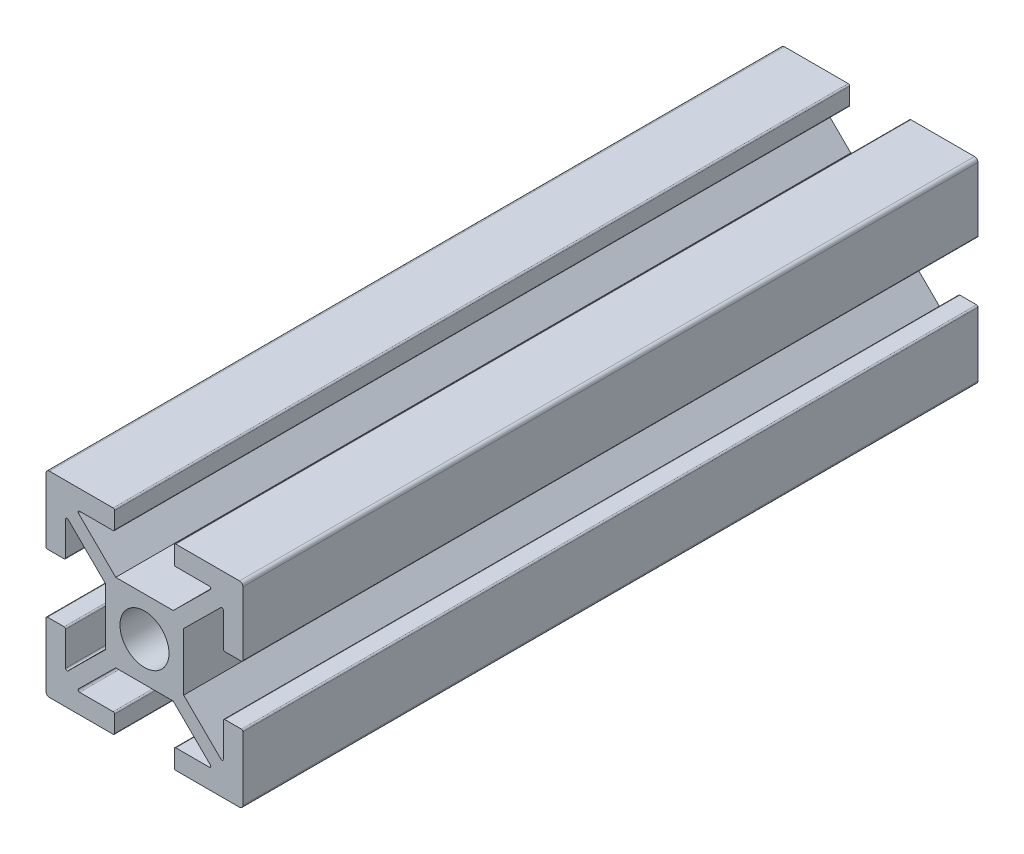
SolidWorks part; units mm, degrees
ref_plane "Front Plane" through (0, 0, 0) normal (0, 0, 1) x (1, 0, 0)
ref_plane "Top Plane" through (0, 0, 0) normal (0, 1, 0) x (1, 0, 0)
ref_plane "Right Plane" through (0, 0, 0) normal (1, 0, 0) x (0, 0, -1)
sketch "Sketch1" plane through (0, 0, 0) normal (0, 0, 1) x (1, 0, 0)
  line L0 (-7.4274, 2.1557) -> (-5.7274, 2.1557)
  line L1 (-0.7274, 9.1557) -> (-7.2274, 9.1557)
  line L2 (-7.5774, 2.3057) -> (-7.5774, 8.8057)
  line L3 (5.4021, 3.1557) -> (-0.4643, 3.1557)
  line L4 (-1.5311, -3.7897) -> (-1.5311, 2.1011)
  line L5 (-5.5774, 2.3057) -> (-5.5774, 5.7419)
  line L6 (-4.1455, 7.1557) -> (-0.7274, 7.1557)
  line L7 (-0.5774, 7.3057) -> (-0.5774, 9.0057)
  line L8 (-5.5774, 7.1557) -> (-1.5311, 3.1557) construction
  line L9 (-5.3219, 5.8486) -> (-1.5311, 2.1011)
  line L10 (-4.2509, 6.899) -> (-0.4643, 3.1557)
  line L11 (10.5152, 7.1557) -> (6.4689, 3.1557) construction
  line L12 (2.4689, -0.8443) -> (2.4689, 10.8443) construction
  line L13 (2.4689, -0.8443) -> (-12.5152, -0.8443) construction
  line L14 (9.1887, 6.899) -> (5.4021, 3.1557)
  line L15 (10.2598, 5.8486) -> (6.4689, 2.1011)
  line L16 (5.5152, 7.3057) -> (5.5152, 9.0057)
  line L17 (9.0833, 7.1557) -> (5.6652, 7.1557)
  line L18 (10.5152, 2.3057) -> (10.5152, 5.7419)
  line L19 (6.4689, -3.7897) -> (6.4689, 2.1011)
  line L20 (12.5152, 2.3057) -> (12.5152, 8.8057)
  line L21 (5.6652, 9.1557) -> (12.1652, 9.1557)
  line L22 (12.3652, 2.1557) -> (10.6652, 2.1557)
  line L23 (10.5152, -8.8443) -> (6.4689, -4.8443) construction
  line L24 (-5.5774, -8.8443) -> (-1.5311, -4.8443) construction
  line L25 (12.3652, -3.8443) -> (10.6652, -3.8443)
  line L26 (5.6652, -10.8443) -> (12.1652, -10.8443)
  line L27 (12.5152, -3.9943) -> (12.5152, -10.4943)
  line L28 (10.5152, -3.9943) -> (10.5152, -7.4305)
  line L29 (9.0833, -8.8443) -> (5.6652, -8.8443)
  line L30 (5.5152, -8.9943) -> (5.5152, -10.6943)
  line L31 (10.2598, -7.5372) -> (6.4689, -3.7897)
  line L32 (9.1887, -8.5876) -> (5.4021, -4.8443)
  line L33 (-4.2509, -8.5876) -> (-0.4643, -4.8443)
  line L34 (-5.3219, -7.5372) -> (-1.5311, -3.7897)
  line L35 (-0.5774, -8.9943) -> (-0.5774, -10.6943)
  line L36 (-4.1455, -8.8443) -> (-0.7274, -8.8443)
  line L37 (-5.5774, -3.9943) -> (-5.5774, -7.4305)
  line L38 (5.4021, -4.8443) -> (-0.4643, -4.8443)
  line L39 (-7.5774, -3.9943) -> (-7.5774, -10.4943)
  line L40 (-0.7274, -10.8443) -> (-7.2274, -10.8443)
  line L41 (-7.4274, -3.8443) -> (-5.7274, -3.8443)
  circle A0 centre (2.4689, -0.8443) radius 2.5
  arc A1 (-7.5774, 8.8057) -> (-7.2274, 9.1557) centre (-7.2274, 8.8057) cw
  arc A2 (-7.4274, 2.1557) -> (-7.5774, 2.3057) centre (-7.4274, 2.3057) cw
  arc A3 (-5.7274, 2.1557) -> (-5.5774, 2.3057) centre (-5.7274, 2.3057) ccw
  arc A4 (-0.7274, 9.1557) -> (-0.5774, 9.0057) centre (-0.7274, 9.0057) cw
  arc A5 (-0.7274, 7.1557) -> (-0.5774, 7.3057) centre (-0.7274, 7.3057) ccw
  arc A6 (-4.2509, 6.899) -> (-4.1455, 7.1557) centre (-4.1455, 7.0057) cw
  arc A7 (-5.3219, 5.8486) -> (-5.5774, 5.7419) centre (-5.4274, 5.7419) ccw
  arc A8 (10.2598, 5.8486) -> (10.5152, 5.7419) centre (10.3652, 5.7419) cw
  arc A9 (9.1887, 6.899) -> (9.0833, 7.1557) centre (9.0833, 7.0057) ccw
  arc A10 (5.6652, 7.1557) -> (5.5152, 7.3057) centre (5.6652, 7.3057) cw
  arc A11 (5.6652, 9.1557) -> (5.5152, 9.0057) centre (5.6652, 9.0057) ccw
  arc A12 (10.6652, 2.1557) -> (10.5152, 2.3057) centre (10.6652, 2.3057) cw
  arc A13 (12.3652, 2.1557) -> (12.5152, 2.3057) centre (12.3652, 2.3057) ccw
  arc A14 (12.5152, 8.8057) -> (12.1652, 9.1557) centre (12.1652, 8.8057) ccw
  arc A15 (12.5152, -10.4943) -> (12.1652, -10.8443) centre (12.1652, -10.4943) cw
  arc A16 (12.3652, -3.8443) -> (12.5152, -3.9943) centre (12.3652, -3.9943) cw
  arc A17 (10.6652, -3.8443) -> (10.5152, -3.9943) centre (10.6652, -3.9943) ccw
  arc A18 (5.6652, -10.8443) -> (5.5152, -10.6943) centre (5.6652, -10.6943) cw
  arc A19 (5.6652, -8.8443) -> (5.5152, -8.9943) centre (5.6652, -8.9943) ccw
  arc A20 (9.1887, -8.5876) -> (9.0833, -8.8443) centre (9.0833, -8.6943) cw
  arc A21 (10.2598, -7.5372) -> (10.5152, -7.4305) centre (10.3652, -7.4305) ccw
  arc A22 (-5.3219, -7.5372) -> (-5.5774, -7.4305) centre (-5.4274, -7.4305) cw
  arc A23 (-4.2509, -8.5876) -> (-4.1455, -8.8443) centre (-4.1455, -8.6943) ccw
  arc A24 (-0.7274, -8.8443) -> (-0.5774, -8.9943) centre (-0.7274, -8.9943) cw
  arc A25 (-0.7274, -10.8443) -> (-0.5774, -10.6943) centre (-0.7274, -10.6943) ccw
  arc A26 (-5.7274, -3.8443) -> (-5.5774, -3.9943) centre (-5.7274, -3.9943) cw
  arc A27 (-7.4274, -3.8443) -> (-7.5774, -3.9943) centre (-7.4274, -3.9943) ccw
  arc A28 (-7.5774, -10.4943) -> (-7.2274, -10.8443) centre (-7.2274, -10.4943) ccw
  point P27 (5.5152, 7.1557)
  point P28 (12.5152, -10.8443)
  point P47 (6.4689, -0.8443)
  point P57 (2.4689, 3.1557)
  point P59 (5.5152, 9.1557)
  point P60 (10.5152, 2.1557)
  point P61 (12.5152, 2.1557)
  point P62 (12.5152, 9.1557)
  point P112 (-1.5311, -0.8443)
  point P113 (12.5152, -3.8443)
  point P114 (10.5152, -3.8443)
  point P115 (5.5152, -10.8443)
  point P116 (2.4689, -4.8443)
  point P117 (-0.5774, -8.8443)
  point P118 (-0.5774, -10.8443)
  point P119 (-5.5774, -3.8443)
  point P120 (5.5152, -8.8443)
  point P121 (-7.5774, -3.8443)
  point P122 (-7.5774, -10.8443)
  dimension "D3" = 0.35
  dimension "D4" = 0.15
  dimension "D5" = 0.15
  dimension "D6" = 0.15
  dimension "D7" = 0.15
  dimension "D8" = 0.15
  dimension "D9" = 0.15
  dimension "D1" = 0.75
  dimension "D2" = 0.75
extrude "Boss-Extrude1" add sketch "Sketch1" along normal blind 75
